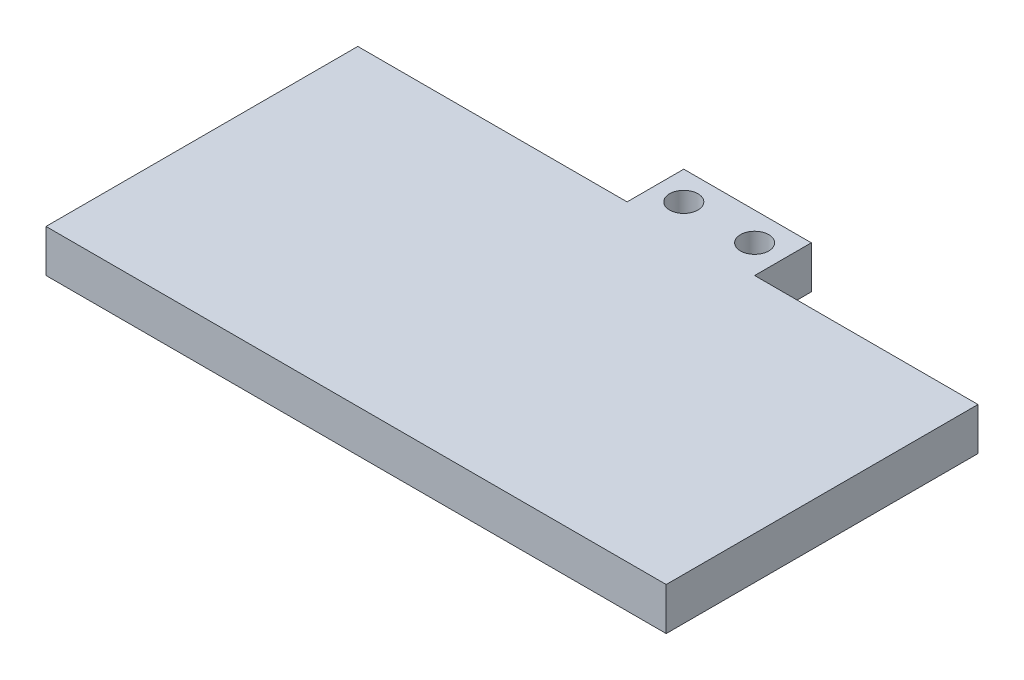
SolidWorks part; units mm, degrees
ref_plane "Front Plane" through (0, 0, 0) normal (0, 0, 1) x (1, 0, 0)
ref_plane "Top Plane" through (0, 0, 0) normal (0, 1, 0) x (1, 0, 0)
ref_plane "Right Plane" through (0, 0, 0) normal (1, 0, 0) x (0, 0, -1)
sketch "Sketch1" plane through (0, 0, 0) normal (0, 1, 0) x (1, 0, 0)
  line L1 (0, 0) -> (277.876, 0)
  line L2 (0, 0) -> (0, 139.7)
  line L3 (0, 139.7) -> (277.876, 139.7)
  line L4 (277.876, 0) -> (277.876, 139.7)
  dimension "D1" = 139.7
  dimension "D2" = 277.876
extrude "Boss-Extrude2" add sketch "Sketch1" along normal blind 19.05
sketch "Sketch2" plane through (0, 19.05, 0) normal (0, 1, 0) x (1, 0, 0)
  line L0 (277.876, 139.7) -> (0, 139.7) construction
  line L1 (120.65, 139.7) -> (177.8, 139.7)
  line L2 (120.65, 139.7) -> (120.65, 165.1)
  line L3 (120.65, 165.1) -> (177.8, 165.1)
  line L4 (177.8, 139.7) -> (177.8, 165.1)
  line L5 (0, 139.7) -> (0, 0) construction
  circle A0 centre (133.35, 152.4) radius 6.35
  circle A1 centre (165.1, 152.4) radius 6.35
  point P10 (177.8, 152.4)
  dimension "D1" = 12.7
  dimension "D2" = 31.75
  dimension "D3" = 12.7
  dimension "D4" = 12.7
  dimension "D5" = 25.4
  dimension "D6" = 120.65
  dimension "D7" = 12.7
  dimension "D8" = 57.15
extrude "Boss-Extrude3" add sketch "Sketch2" against normal blind 19.05
